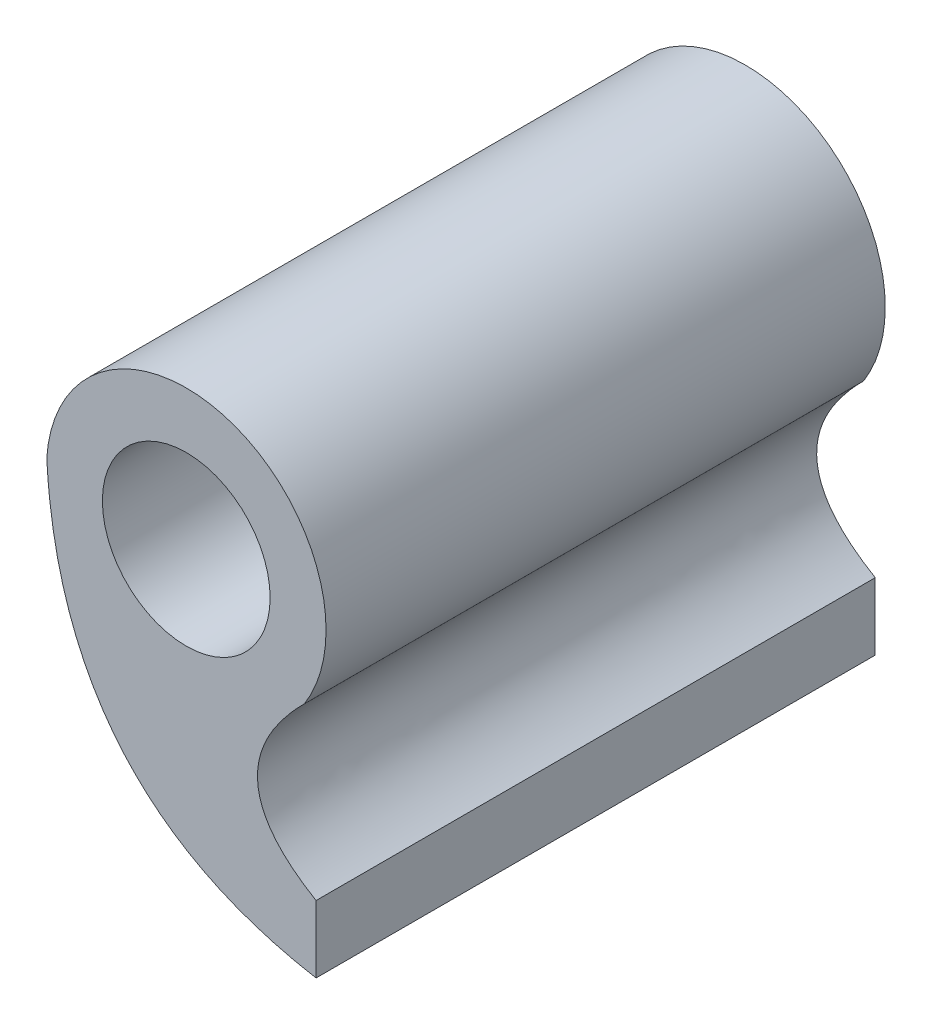
SolidWorks part; units mm, degrees
material "51 Si 7"
ref_plane "Ön Düzlem" through (0, 0, 0) normal (0, 0, 1) x (1, 0, 0)
ref_plane "Üst Düzlem" through (0, 0, 0) normal (0, 1, 0) x (1, 0, 0)
ref_plane "Sağ Düzlem" through (0, 0, 0) normal (1, 0, 0) x (0, 0, -1)
sketch "Sketch2" plane through (0, 0, 0) normal (0, 0, 1) x (1, 0, 0)
  line L0 (0, 0) -> (0, 12)
  arc A0 (-2.0789, 41.4323) -> (-47.4075, 48.4929) centre (-23.2129, 54.7873) ccw
  circle A1 centre (-23.2129, 54.7873) radius 15
  spline S0 degree 2 poles (0, 12) (-19.8555, 23.7011) (-2.0789, 41.4323) knots 0 0 0 1 1 1
  spline S1 degree 3 poles (0, 0) (-30.3671, 5.3006) (-46.4202, 24.1093) (-48.1591, 56.4259) knots 0 0 0 0 0.900808 0.900808 0.900808 0.900808
extrude "Boss-Extrude3" add sketch "Sketch2" along normal blind 100
